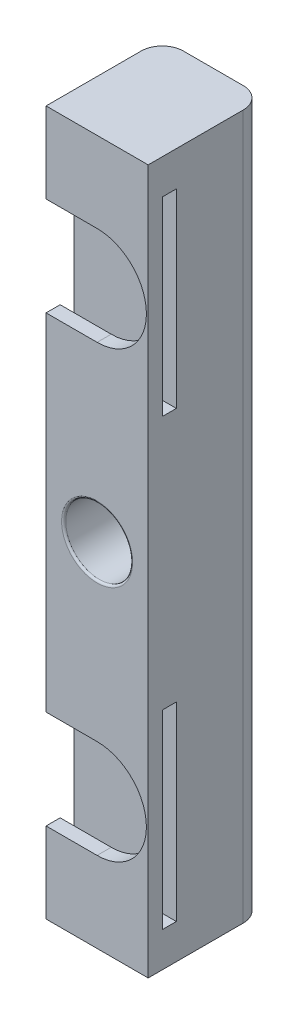
SolidWorks part; units mm, degrees
ref_plane "Front Plane" through (0, 0, 0) normal (1, 0, 0) x (0, 1, 0)
ref_plane "Top Plane" through (0, 0, 0) normal (0, 0, 1) x (0, 1, 0)
ref_plane "Right Plane" through (0, 0, 0) normal (0, 1, 0) x (-1, 0, 0)
sketch "Sketch7" plane through (0, 0, 0) normal (0, 0, 1) x (0, 1, 0)
  line L1 (-50, -7.25) -> (50, -7.25)
  line L2 (-50, -7.25) -> (-50, 7.25)
  line L3 (-50, 7.25) -> (50, 7.25)
  line L4 (50, -7.25) -> (50, 7.25)
  line L5 (-50, -7.25) -> (50, 7.25) construction
  line L6 (-50, 7.25) -> (50, -7.25) construction
  point P0 (0, 0)
  dimension "D1" = 14.5
  dimension "D2" = 100
extrude "Boss-Extrude1" add sketch "Sketch7" along normal blind 16.5
sketch "Sketch8" plane through (0, 0, 16.5) normal (0, 0, 1) x (0, -1, 0)
  circle A0 centre (0, 0) radius 4.75
  dimension "D1" = 9.5
extrude "Cut-Extrude2" cut sketch "Sketch8" against normal blind 16
sketch "Sketch9" plane through (0, 0, 16.5) normal (0, 0, 1) x (1, 0, 0)
  line L0 (0, 0) -> (0, -31.55) construction
  line L2 (-13.5, -45.05) -> (13.5, -45.05)
  line L3 (-13.5, -45.05) -> (-13.5, -18.05)
  line L4 (-13.5, -18.05) -> (13.5, -18.05)
  line L5 (13.5, -45.05) -> (13.5, -18.05)
  line L6 (-13.5, -45.05) -> (13.5, -18.05) construction
  line L7 (-13.5, -18.05) -> (13.5, -45.05) construction
  dimension "D1" = 31.55
  dimension "D2" = 27
extrude "Cut-Extrude3" cut sketch "Sketch9" against normal blind 2 from offset 2 offset against normal yes
sketch "Sketch10" plane through (0, 0, 16.5) normal (0, 0, 1) x (1, 0, 0)
  line L0 (0, 0) -> (0, -31.55) construction
  line L1 (0, -24.55) -> (-7.25, -24.55)
  line L2 (-7.25, 50) -> (-7.25, -50) construction
  line L3 (-7.25, -24.55) -> (-7.25, -38.55)
  line L4 (0, -38.55) -> (-7.25, -38.55)
  arc A0 (0, -38.55) -> (0, -24.55) centre (0, -31.55) ccw
  dimension "D2" = 14
  dimension "D1" = 31.55
extrude "Cut-Extrude4" cut sketch "Sketch10" against normal blind 2
mirror "Mirror1" about plane through (0, 0, 0) normal (0, 1, 0) of "Cut-Extrude3"
mirror "Mirror2" about plane through (0, 0, 0) normal (0, 1, 0) of "Cut-Extrude4"
fillet "Fillet1" radius 3 1 edges at (-7.25, 0, 0)
fillet "Fillet2" radius 3 1 edges at (7.25, 0, 0)
fillet "Fillet3" radius 0.3 1 edges at (4.75, 0, 16.5)
